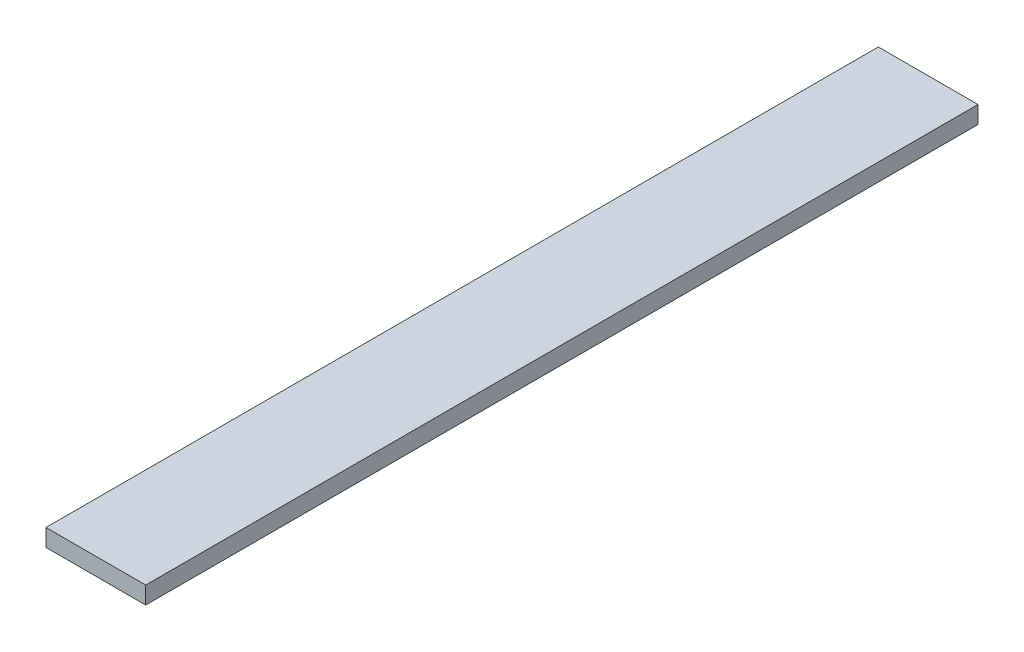
SolidWorks part; units mm, degrees
ref_plane "Front Plane" through (0, 0, 0) normal (0, 0, 1) x (1, 0, 0)
ref_plane "Top Plane" through (0, 0, 0) normal (0, 1, 0) x (1, 0, 0)
ref_plane "Right Plane" through (0, 0, 0) normal (1, 0, 0) x (0, 0, -1)
sketch "Sketch1" plane through (0, 0, 0) normal (0, 0, 1) x (1, 0, 0)
  line L1 (-57.5, 10) -> (57.5, 10)
  line L2 (-57.5, 10) -> (-57.5, -10)
  line L3 (-57.5, -10) -> (57.5, -10)
  line L4 (57.5, 10) -> (57.5, -10)
  line L5 (-57.5, 10) -> (57.5, -10) construction
  line L6 (-57.5, -10) -> (57.5, 10) construction
  point P0 (0, 0)
extrude "Boss-Extrude1" add sketch "Sketch1" along normal blind 960 contours L1 L4 L3 L2
